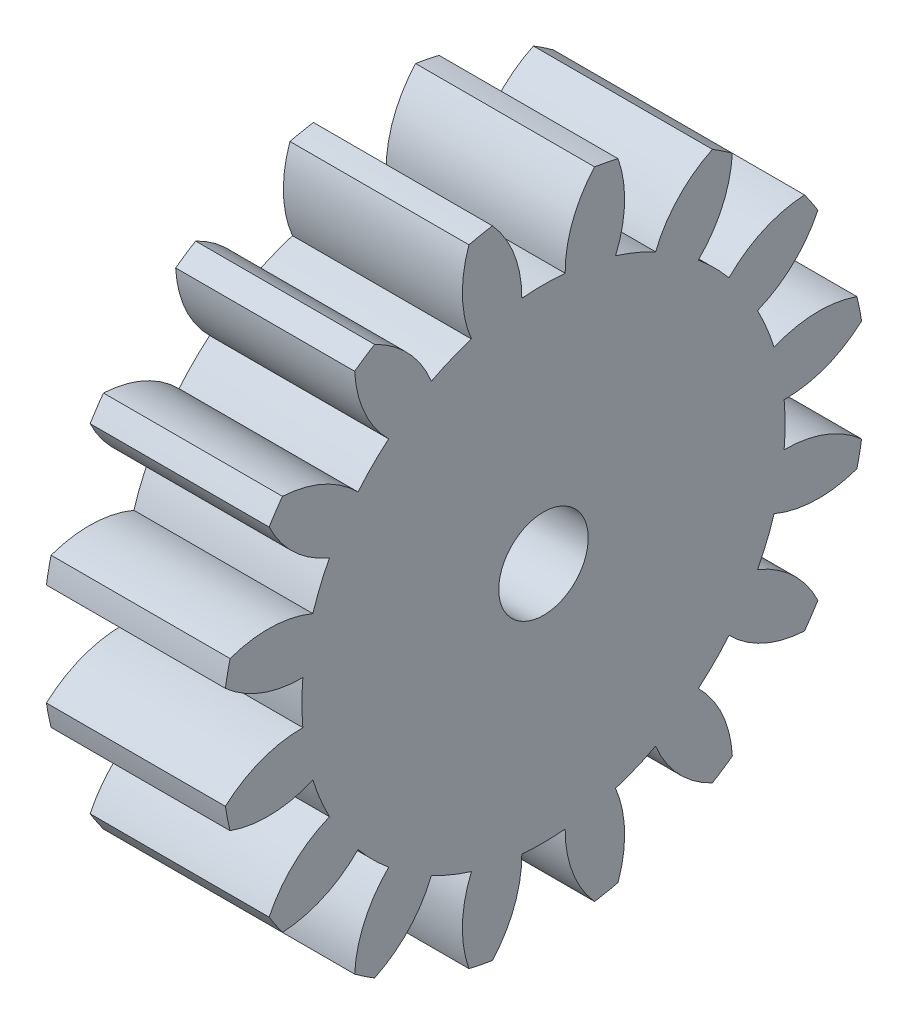
SolidWorks part; units mm, degrees
ref_plane "Plane1" through (0, 0, 0) normal (0, 0, 1) x (1, 0, 0)
ref_plane "Plane2" through (0, 0, 0) normal (0, 1, 0) x (1, 0, 0)
ref_plane "Plane3" through (0, 0, 0) normal (1, 0, 0) x (0, 0, -1)
other "Configuration Table"
sketch "HoldingSke" plane through (0, 0, 0) normal (0, 1, 0) x (1, 0, 0)
  line L0 (0, 0) -> (0.4806, -0.1378)
  line L1 (-15, 0) -> (100, 0) construction
  line L2 (0, 0) -> (-2.1039, 2.3779)
  line L3 (0, 0) -> (-11.863, 4.5341)
  line L4 (0, 0) -> (8.3015, 2.3804)
  line L5 (0, 0) -> (-46.8476, -17.4728)
  line L6 (0, 0) -> (-8.2896, -5.593)
  line L7 (-2.1039, 2.3779) -> (8.6586, 51.2059)
  line L8 (-76.2, 54.61) -> (-75.3, 54.61)
  line L9 (-67.7845, 28.3722) -> (-49.3413, 33.142)
  line L10 (-76.2, 71.12) -> (104.1128, 71.12)
  line L11 (0, 0) -> (-10, 0)
  line L12 (-76.2, 101.6) -> (-76.133, 101.6)
  line L13 (24.9733, 27.94) -> (52.9518, 28.4284)
  line L14 (24.9733, 27.94) -> (24.9743, 27.94)
  line L15 (24.9733, 27.94) -> (100.4006, 29.5858)
  line L16 (-63.627, -2) -> (-12.827, -2)
  circle A0 centre (0, 0) radius 2.5
  circle A1 centre (0, 0) radius 13.499
  circle A2 centre (0, 0) radius 37.5
  circle A3 centre (0, 0) radius 2.5
  dimension "Hub_dia" = 75
  dimension "Bore" = 5
  dimension "MBD" = 5
  dimension "Overall_len" = 50
  dimension "Thickness" = 10
  dimension "OAL" = 50.0001
  dimension "T_dim" = 0.9
  dimension "Ap" = 14.5
  dimension "H" = 19.05
  dimension "Pitch_radius" = 180.3128
  dimension "Width" = 10
  dimension "Addendum_fac" = 1
  dimension "Dedendum_fac" = 1.25
  dimension "Clearance_fac" = 0.25
  dimension "Dedendum_add" = 0.001
sketch "BasProSke" plane through (0, 0, 0) normal (0, 1, 0) x (1, 0, 0)
  line L0 (-10, 0) -> (60, 0) construction
  line L1 (0, 0) -> (0, 18)
  line L2 (0, 0) -> (10, 0)
  line L3 (10, 0) -> (10, 18)
  line L4 (10, 18) -> (0, 18)
  dimension "Thickness" = 10
revolve "Base-Revolve" add sketch "BasProSke" angle 360 about L0
sketch "TooCutSke" plane through (0, 0, 0) normal (1, 0, 0) x (0, 0, -1)
  line L1 (0, 0) -> (0, 107) construction
  line L2 (0, 0) -> (-1.6854, 15.911) construction
  line L3 (0, 0) -> (-6.2172, 31.2558) construction
  line L4 (-1.6854, 15.911) -> (-3.1086, 15.6279) construction
  arc A0 (1.2108, 13.4446) -> (-1.2108, 13.4446) centre (0, 0) ccw
  arc A1 (2.8732, 17.7949) -> (-2.8732, 17.7949) centre (0, 0) ccw
  circle A2 centre (0, 0) radius 16 construction
  circle A3 centre (0, 0) radius 15.4904 construction
  arc A4 (-1.2108, 13.4446) -> (-2.8732, 17.7949) centre (-7.6106, 13.4918) ccw
  arc A5 (2.8732, 17.7949) -> (1.2108, 13.4446) centre (7.6106, 13.4918) ccw
extrude "ToothCut" cut sketch "TooCutSke" along normal through all
fillet "Breaks" [suppressed] radius 0.04
fillet "RootFillets" [suppressed] radius 0.501
pattern_circular "TeethCuts" count 16 every 22.5 about axis through (-10, 0, 0) along (1, 0, 0) of "ToothCut", "RootFillets", "Breaks"
sketch "HubNeaOneSke" plane through (0, 0, 0) normal (-1, 0, 0) x (0, 0, 1)
  circle A0 centre (0, 0) radius 13.499
extrude "HubNearOne" [suppressed] add sketch "HubNeaOneSke" along normal blind 40.0001
sketch "HubNeaBotSke" plane through (0, 0, 0) normal (-1, 0, 0) x (0, 0, 1)
  circle A0 centre (0, 0) radius 13.499
extrude "HubNearBoth" [suppressed] add sketch "HubNeaBotSke" along normal blind 20
ref_plane "FarPln" through (10, 0, 0) normal (1, 0, 0) x (0, 0, -1)
sketch "HubFarSke" plane through (10, 0, 0) normal (1, 0, 0) x (0, 0, -1)
  circle A0 centre (0, 0) radius 13.499
extrude "HubFar" [suppressed] add sketch "HubFarSke" along normal blind 20
sketch "BorSke" plane through (0, 0, 0) normal (1, 0, 0) x (0, 0, -1)
  circle A0 centre (0, 0) radius 2.5
  dimension "Diameter" = 5
extrude "Bore" cut sketch "BorSke" along normal mid plane 100.0001
sketch "KeySke" plane through (0, 0, 0) normal (1, 0, 0) x (0, 0, -1)
  line L0 (-1, 0) -> (-1, 3.4)
  line L1 (-1, 3.4) -> (1, 3.4)
  line L2 (1, 3.4) -> (1, 0)
  line L3 (0, 0) -> (0, 34) construction
  line L4 (-1, 0) -> (1, 0)
  dimension "Offset" = 3.4
  dimension "Width" = 2
extrude "Keyway" [suppressed] cut sketch "KeySke" along normal mid plane 100.0001
pattern_circular "Keyway2" [suppressed] count 2 every 90 about axis through (-10, 0, 0) along (1, 0, 0)
equation "' \"Module@HoldingSke\" = 6.35"
equation "' \"Num_teeth@HoldingSke\" = 12"
equation "' \"Ap@HoldingSke\" =  20"
equation "' \"Ap@HoldingSke\" = 20"
equation "' \"Width@HoldingSke\" = 0.5 * 25.4"
equation "' \"Hub_dia@HoldingSke\"= 1 * 25.4"
equation "' \"Hub_dia@HoldingSke\" = 1 * 25.4"
equation "' \"Overall_len@HoldingSke\" = 1.0 * 25.4"
equation "' \"Bore@HoldingSke\" = 0.75 * 25.4"
equation "' \"T_dim@HoldingSke\" = 0.1 * 25.4"
equation "' \"Width@KeySke\" = 0.25 * 25.4"
equation "' \"Show_teeth@HoldingSke\" = 13"
equation "' \"Backlash@HoldingSke\" = 0.009 * 25.4"
equation "' \"Addendum_fac@HoldingSke\" = 1.0"
equation "' \"Dedendum_fac@HoldingSke\" = 1.25"
equation "' \"Dedendum_add@HoldingSke\" = 0.00005 * 25.4"
equation "' \"Clearance_fac@HoldingSke\" = 0.25"
equation "\"Pitch@HoldingSke\" = 1 / \"Module@HoldingSke\""
equation "\"Overcut_dia@TooCutSke\" = (\"Num_teeth@HoldingSke\" + 2 * \"Addendum_fac@HoldingSke\") / \"Pitch@HoldingSke\" + 0.002 * 25.4"
equation "\"Pitch_dia@TooCutSke\" = \"Num_teeth@HoldingSke\" / \"Pitch@HoldingSke\""
equation "\"Base_dia@TooCutSke\" = \"Num_teeth@HoldingSke\" / \"Pitch@HoldingSke\" * cos((\"Ap@HoldingSke\"  * 3.14159265 / 180))"
equation "\"Root_dia@TooCutSke\" = (\"Num_teeth@HoldingSke\" + 2) / \"Pitch@HoldingSke\" - 2 * (\"Addendum_fac@HoldingSke\" + \"Dedendum_fac@HoldingSke\") / \"Pitch@HoldingSke\" - \"Dedendum_add@HoldingSke\" * 2"
equation "\"Half_ang@TooCutSke\" = 180 / \"Num_teeth@HoldingSke\""
equation "\"Half_CT@TooCutSke\" = \"Num_teeth@HoldingSke\" / \"Pitch@HoldingSke\" * sin((3.14159265 / 2 / \"Num_teeth@HoldingSke\")) / 2 - 7 * \"Backlash@HoldingSke\" / 4"
equation "\"Flank_rad@TooCutSke\" = \"Num_teeth@HoldingSke\" / \"Pitch@HoldingSke\" / 5"
equation "\"Radius@RootFillets\" = \"Clearance_fac@HoldingSke\" / \"Pitch@HoldingSke\" + \"Dedendum_add@HoldingSke\""
equation "\"Break_rad@Breaks\" = 0.02 / \"Pitch@HoldingSke\""
equation "\"Thickness@HoldingSke\" = \"Width@HoldingSke\""
equation "\"OAL@HoldingSke\" = \"Thickness@HoldingSke\""
equation "\"MHD@HoldingSke\" = (\"Num_teeth@HoldingSke\" + 2) / \"Pitch@HoldingSke\" - 2 * (\"Addendum_fac@HoldingSke\" + \"Dedendum_fac@HoldingSke\")  / \"Pitch@HoldingSke\" - \"Dedendum_add@HoldingSke\" * 2"
equation "\"MBD@HoldingSke\" = (\"Num_teeth@HoldingSke\" + 2) / \"Pitch@HoldingSke\" - 2 * (\"Addendum_fac@HoldingSke\" + \"Dedendum_fac@HoldingSke\")  / \"Pitch@HoldingSke\" - \"Dedendum_add@HoldingSke\" * 2 - 0.002 * 25.4"
equation "\"MHD@HoldingSke\" = ((sgn( \"MHD@HoldingSke\" - \"Hub_dia@HoldingSke\" )-1)*( \"MHD@HoldingSke\" - \"Hub_dia@HoldingSke\" ))/-2+ \"Hub_dia@HoldingSke\""
equation "\"MBD@HoldingSke\" = ((sgn( \"MBD@HoldingSke\" - \"Bore@HoldingSke\" )-1)*( \"MBD@HoldingSke\" - \"Bore@HoldingSke\" ))/-2+ \"Bore@HoldingSke\""
equation "\"OAL@HoldingSke\" = ((sgn( \"OAL@HoldingSke\" - \"Overall_len@HoldingSke\" )+1)*( \"OAL@HoldingSke\" - \"Overall_len@HoldingSke\" ))/2 + \"Overall_len@HoldingSke\" + 0.000002 * 25.4"
equation "\"Num_teeth@TeethCuts\" = int( \"Show_teeth@HoldingSke\" ) + 1"
equation "\"Num_teeth@TeethCuts\" = ((sgn( \"Num_teeth@TeethCuts\" - \"Num_teeth@HoldingSke\" )-1)*( \"Num_teeth@TeethCuts\" - \"Num_teeth@HoldingSke\" ))/-2+ \"Num_teeth@HoldingSke\""
equation "\"Num_teeth@TeethCuts\" = ((sgn( \"Num_teeth@TeethCuts\" - 2.0)+1)*( \"Num_teeth@TeethCuts\" - 2.0))/2 +2.0"
equation "\"Angle@TeethCuts\" = 360.0 / \"Num_teeth@HoldingSke\""
equation "\"Diameter@BasProSke\" = (\"Num_teeth@HoldingSke\" + 2 * \"Addendum_fac@HoldingSke\") / \"Pitch@HoldingSke\""
equation "\"Thickness@BasProSke\"  = \"Thickness@HoldingSke\""
equation "' \"Fillet_rad@BasProSke\" =  \"Thickness@HoldingSke\" * 0.05"
equation "' \"Fillet_rad@BasProSke\" = \"Thickness@HoldingSke\" * 0.05"
equation "\"MHD@HoldingSke\" = ((sgn( \"MHD@HoldingSke\" - \"Root_dia@TooCutSke\" )-1)*( \"MHD@HoldingSke\" - \"Root_dia@TooCutSke\" ))/-2+ \"Root_dia@TooCutSke\""
equation "\"Diameter@HubNeaOneSke\" = \"MHD@HoldingSke\""
equation "\"Length@HubNearOne\" = \"OAL@HoldingSke\" - \"Thickness@BasProSke\""
equation "\"Diameter@HubNeaBotSke\" = \"MHD@HoldingSke\""
equation "\"Length@HubNearBoth\" = ( \"OAL@HoldingSke\" - \"Thickness@BasProSke\" ) / 2.0"
equation "\"Thickness@FarPln\" = \"Thickness@BasProSke\""
equation "\"Diameter@HubFarSke\" = \"MHD@HoldingSke\""
equation "\"Length@HubFar\" = ( \"OAL@HoldingSke\" - \"Thickness@BasProSke\" ) / 2.0"
equation "\"Diameter@BorSke\" = \"MBD@HoldingSke\""
equation "\"D1@Bore\" = \"OAL@HoldingSke\" * 2.0"
equation "\"D1@Keyway\" = \"OAL@HoldingSke\" * 2.0"
equation "\"Offset@KeySke\" = \"T_dim@HoldingSke\" + \"MBD@HoldingSke\" / 2.0"
